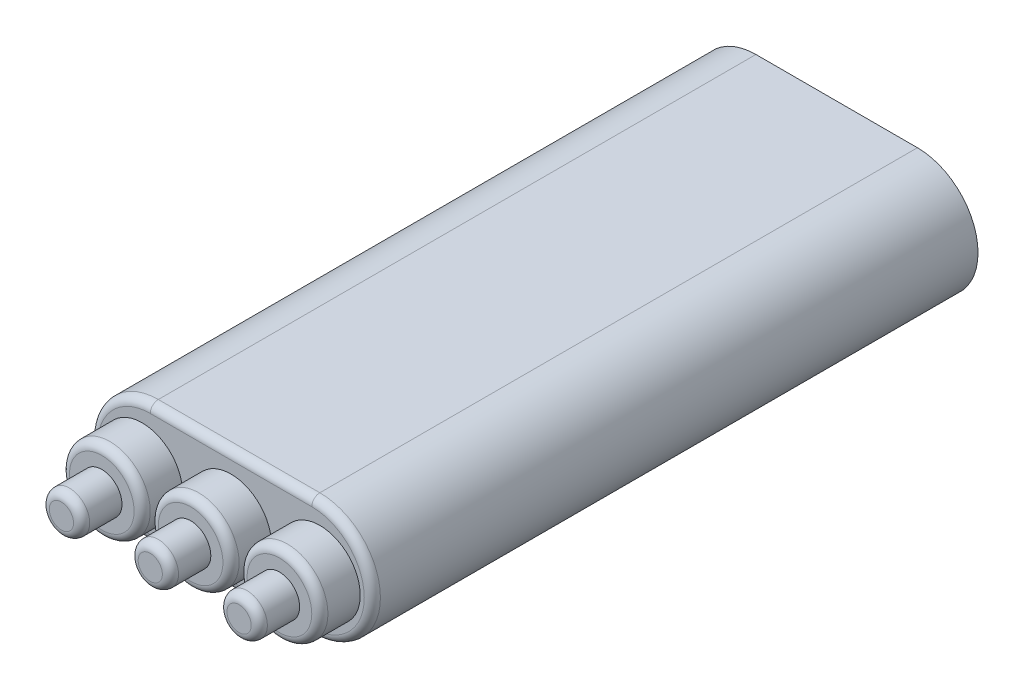
SolidWorks part; units mm, degrees
ref_plane "Спереди" through (0, 0, 0) normal (0, 0, 1) x (1, 0, 0)
ref_plane "Сверху" through (0, 0, 0) normal (0, 1, 0) x (1, 0, 0)
ref_plane "Справа" through (0, 0, 0) normal (1, 0, 0) x (0, 0, -1)
sketch "Эскиз1" plane through (0, 0, 0) normal (0, 0, 1) x (1, 0, 0)
  line L0 (-2, 0) -> (2, 0) construction
  line L1 (-2, 1.5) -> (2, 1.5)
  line L2 (-2, -1.5) -> (2, -1.5)
  arc A0 (-2, 1.5) -> (-2, -1.5) centre (-2, 0) ccw
  arc A1 (2, -1.5) -> (2, 1.5) centre (2, 0) ccw
  point P2 (0, 0)
  dimension "D1" = 1.5
  dimension "D2" = 4
extrude "Бобышка-Вытянуть1" add sketch "Эскиз1" along normal blind 15
sketch "Эскиз2" plane through (0, 0, 15) normal (0, 0, 1) x (1, 0, 0)
  line L0 (-3.9736, 0) -> (3.8125, 0) construction
  circle A0 centre (-2.2, 0) radius 1
  circle A1 centre (0, 0) radius 1
  circle A2 centre (2.2, 0) radius 1
  dimension "D1" = 2
  dimension "D2" = 2
  dimension "D3" = 2
  dimension "D4" = 2.2
  dimension "D5" = 2.2
extrude "Бобышка-Вытянуть2" add sketch "Эскиз2" along normal blind 1 separate body
sketch "Эскиз4" plane through (0, 0, 16) normal (0, 0, 1) x (1, 0, 0)
  circle A0 centre (0, 0) radius 0.5
  circle A1 centre (-2.2, 0) radius 0.5
  circle A2 centre (2.2, 0) radius 0.5
  dimension "D1" = 1
  dimension "D2" = 1
  dimension "D3" = 1
extrude "Бобышка-Вытянуть3" add sketch "Эскиз4" along normal blind 1 separate body
fillet "Скругление1" radius 0.2 4 edges at (0, 1.5, 15) (3.5, 0, 15) (0, -1.5, 15) (-3.5, 0, 15)
fillet "Скругление2" radius 0.2 1 edges at (-1.2, 0, 16)
fillet "Скругление3" radius 0.2 1 edges at (1, 0, 16)
fillet "Скругление4" radius 0.2 1 edges at (3.2, 0, 16)
fillet "Скругление5" radius 0.2 1 edges at (-1.7, 0, 17)
fillet "Скругление6" radius 0.2 1 edges at (0.5, 0, 17)
fillet "Скругление7" radius 0.2 1 edges at (2.7, 0, 17)
